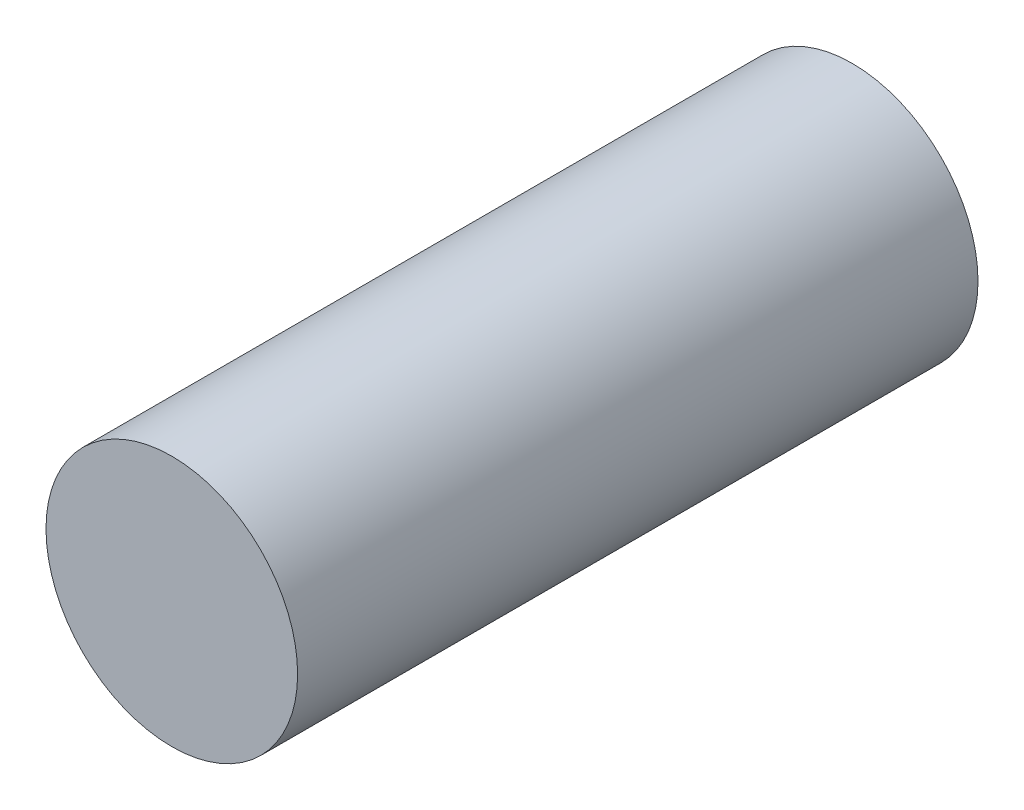
SolidWorks part; units mm, degrees
ref_plane "Front Plane" through (0, 0, 0) normal (0, 0, 1) x (1, 0, 0)
ref_plane "Top Plane" through (0, 0, 0) normal (0, 1, 0) x (1, 0, 0)
ref_plane "Right Plane" through (0, 0, 0) normal (1, 0, 0) x (0, 0, -1)
sketch "Sketch1" plane through (0, 0, 0) normal (0, 0, 1) x (1, 0, 0)
  circle A0 centre (0, 0) radius 1.2446
  dimension "D1" = 2.4892
extrude "Boss-Extrude1" add sketch "Sketch1" along normal blind 6.731
sketch "Sketch2" plane through (0, 0, 6.731) normal (0, 0, 1) x (1, 0, 0)
  arc A0 (-1.2446, 0) -> (1.2446, 0) centre (0, 0) cw
  circle A2 centre (0, 0) radius 1.2446 construction
